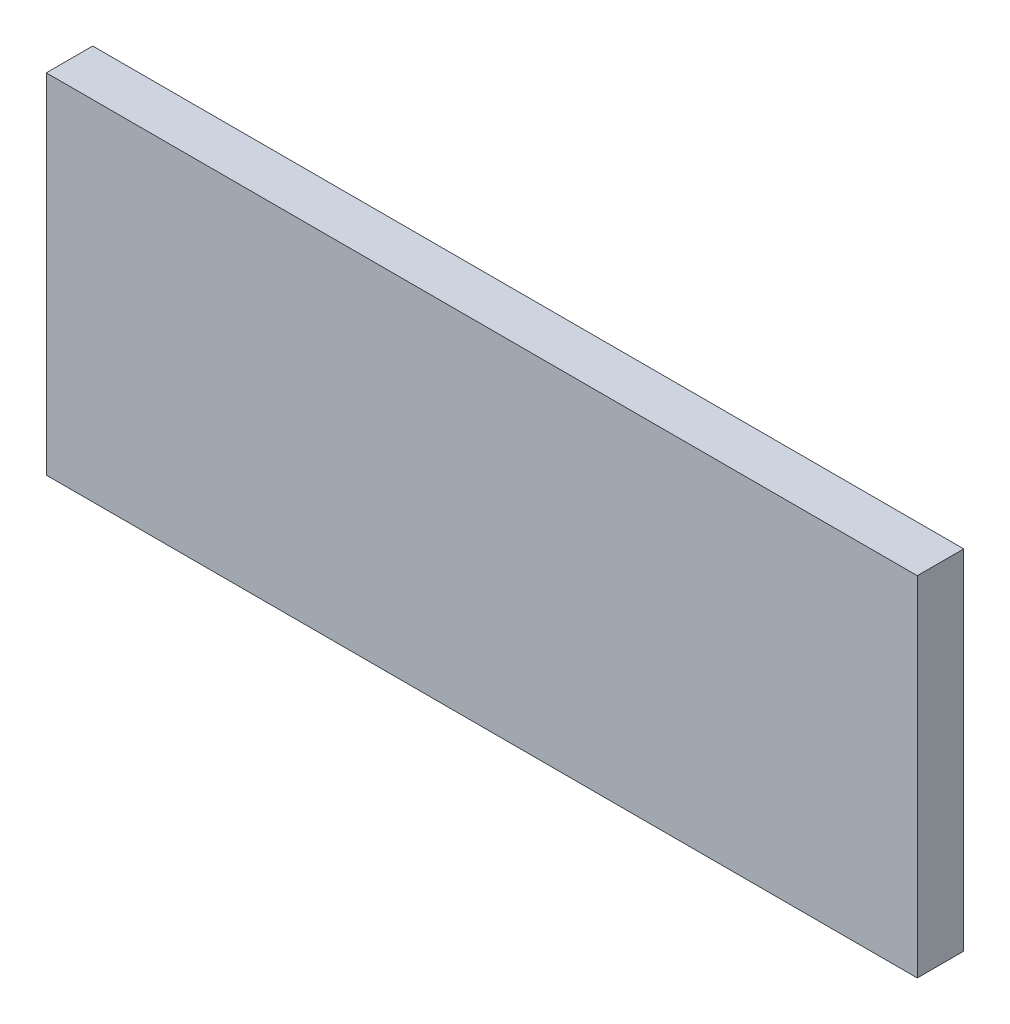
SolidWorks part; units mm, degrees
ref_plane "前视基准面" through (0, 0, 0) normal (0, 0, 1) x (1, 0, 0)
ref_plane "上视基准面" through (0, 0, 0) normal (0, 1, 0) x (1, 0, 0)
ref_plane "右视基准面" through (0, 0, 0) normal (1, 0, 0) x (0, 0, -1)
sketch "草图1" plane through (0, 0, 0) normal (0, 0, 1) x (1, 0, 0)
  line L1 (0, 0) -> (150, 0)
  line L2 (0, 0) -> (0, 60)
  line L3 (0, 60) -> (150, 60)
  line L4 (150, 0) -> (150, 60)
  dimension "D1" = 60
  dimension "D2" = 150
extrude "凸台-拉伸1" add sketch "草图1" along normal blind 8
